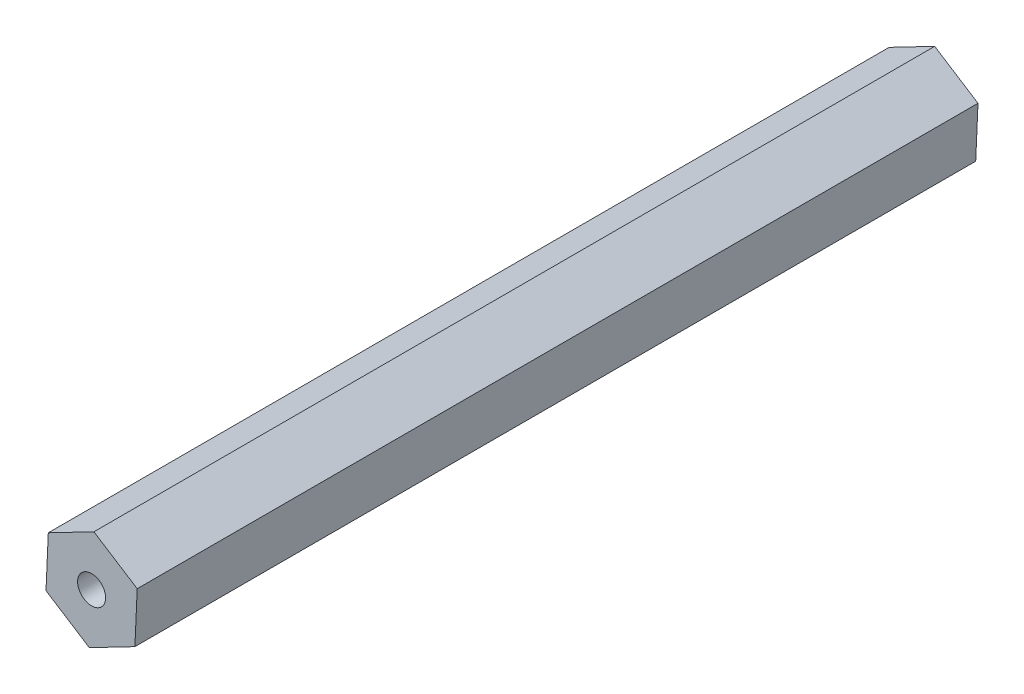
SolidWorks part; units mm, degrees
ref_plane "Front Plane" through (0, 0, 0) normal (0, 0, 1) x (1, 0, 0)
ref_plane "Top Plane" through (0, 0, 0) normal (0, 1, 0) x (1, 0, 0)
ref_plane "Right Plane" through (0, 0, 0) normal (1, 0, 0) x (0, 0, -1)
sketch "Sketch1" plane through (0, 0, 0) normal (0, 0, 1) x (1, 0, 0)
  line L1 (2.3177, -1.4801) -> (2.4406, 1.2672)
  line L2 (2.4406, 1.2672) -> (0.1229, 2.7473)
  line L3 (0.1229, 2.7473) -> (-2.3177, 1.4801)
  line L4 (-2.3177, 1.4801) -> (-2.4406, -1.2672)
  line L5 (-2.4406, -1.2672) -> (-0.1229, -2.7473)
  line L6 (-0.1229, -2.7473) -> (2.3177, -1.4801)
  circle A0 centre (0, 0) radius 2.75 construction
  dimension "D1" = 5.5
extrude "Boss-Extrude1" add sketch "Sketch1" along normal blind 45
sketch "Sketch2" plane through (0, 0, 45) normal (0, 0, 1) x (1, 0, 0)
  circle A0 centre (0, 0) radius 0.75
  dimension "D1" = 1.5
extrude "Cut-Extrude1" cut sketch "Sketch2" against normal blind 5
sketch "Sketch3" plane through (0, 0, 0) normal (0, 0, -1) x (-1, 0, 0)
  circle A0 centre (0, 0) radius 0.75
  dimension "D1" = 1.5
extrude "Cut-Extrude2" cut sketch "Sketch3" against normal blind 5
